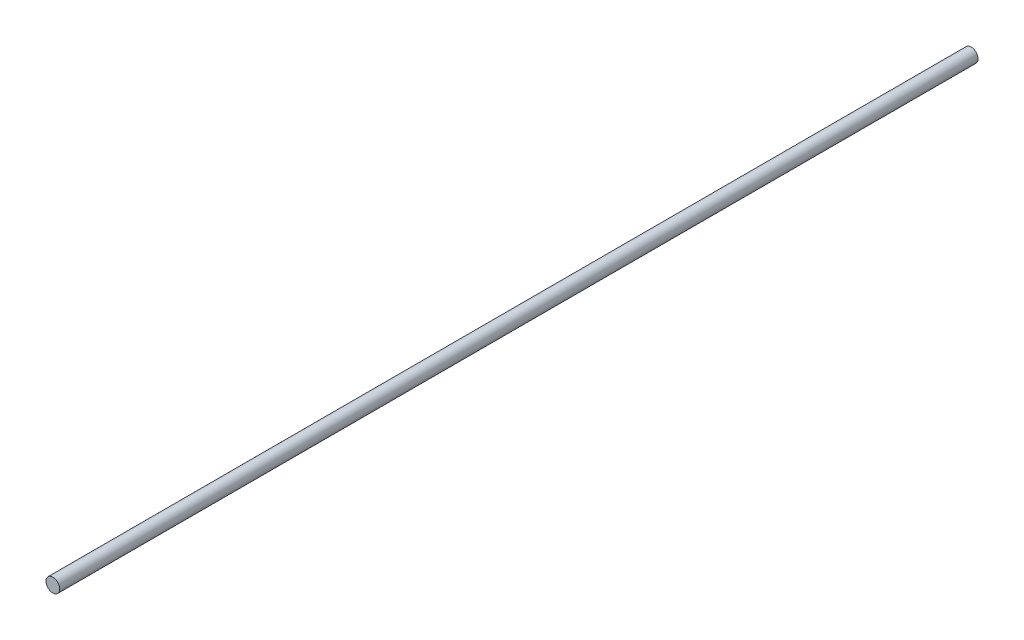
SolidWorks part; units mm, degrees
ref_plane "Front Plane" through (0, 0, 0) normal (0, 0, 1) x (1, 0, 0)
ref_plane "Top Plane" through (0, 0, 0) normal (0, 1, 0) x (1, 0, 0)
ref_plane "Right Plane" through (0, 0, 0) normal (1, 0, 0) x (0, 0, -1)
sketch "Sketch1" plane through (0, 0, 0) normal (0, 0, 1) x (1, 0, 0)
  circle A0 centre (0, 0) radius 4
extrude "Boss-Extrude1" add sketch "Sketch1" along normal mid plane 535.5
